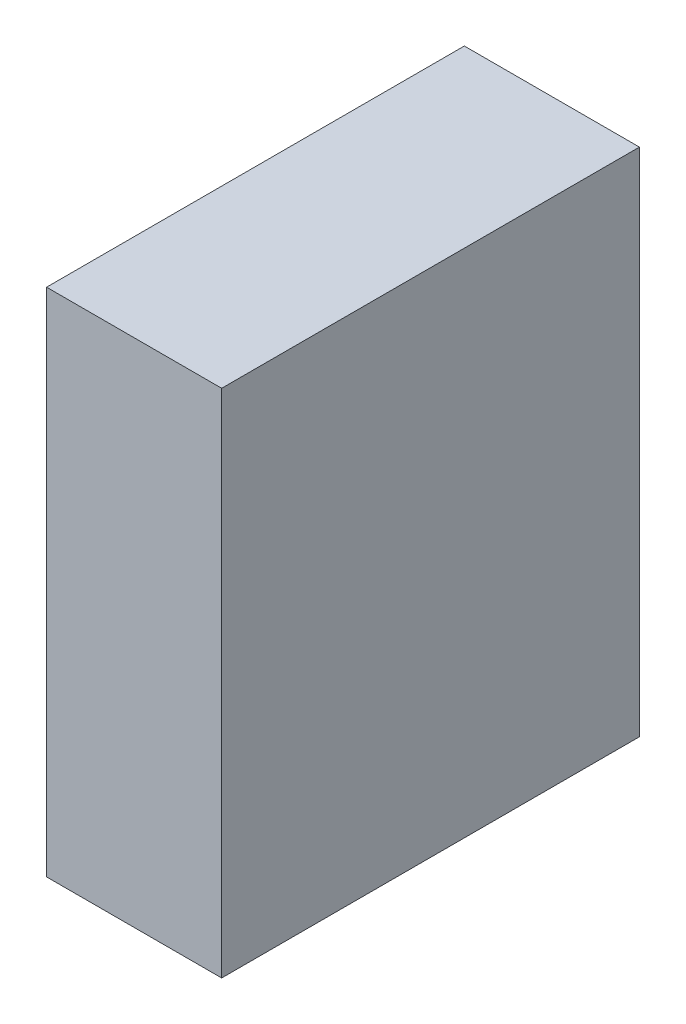
SolidWorks part; units mm, degrees
ref_plane "Front Plane" through (0, 0, 0) normal (0, 0, 1) x (1, 0, 0)
ref_plane "Top Plane" through (0, 0, 0) normal (0, 1, 0) x (1, 0, 0)
ref_plane "Right Plane" through (0, 0, 0) normal (1, 0, 0) x (0, 0, -1)
sketch "Sketch1" plane through (0, 0, 0) normal (1, 0, 0) x (0, 0, -1)
  line L1 (47.231, 6.7021) -> (49.6171, 6.7021)
  line L2 (47.231, 6.7021) -> (47.231, 3.785)
  line L3 (47.231, 3.785) -> (49.6171, 3.785)
  line L4 (49.6171, 6.7021) -> (49.6171, 3.785)
extrude "Boss-Extrude1" add sketch "Sketch1" along normal blind 1
